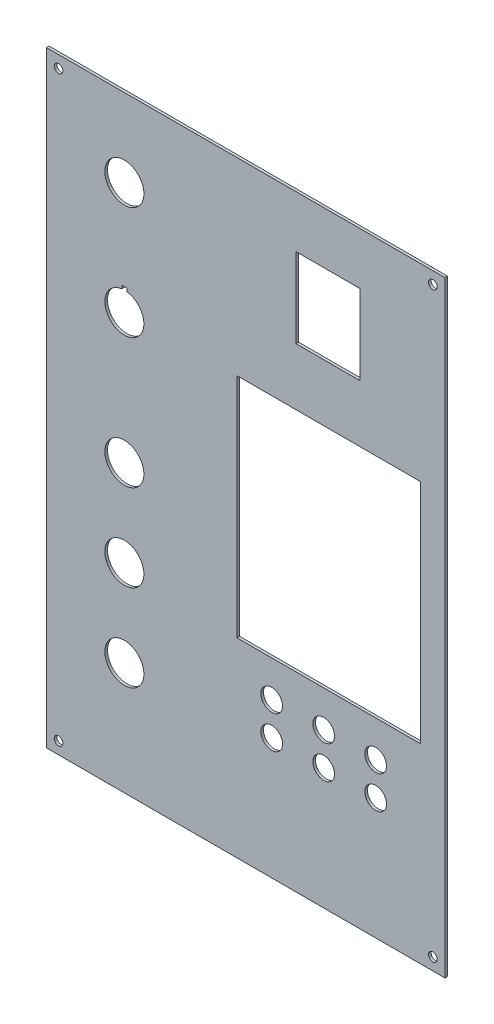
SolidWorks part; units mm, degrees
material "PW80:Md:De:1:18:"
ref_plane "Plan1" through (0, 0, 0) normal (0, 0, 1) x (1, 0, 0)
ref_plane "Plan2" through (0, 0, 0) normal (0, 1, 0) x (1, 0, 0)
ref_plane "Plan3" through (0, 0, 0) normal (1, 0, 0) x (0, 0, -1)
sketch "Esquisse1" plane through (0, 0, 0) normal (0, 0, 1) x (1, 0, 0)
  line L1 (0, 0) -> (230, 0)
  line L2 (0, 0) -> (0, 350)
  line L3 (0, 350) -> (230, 350)
  line L4 (230, 0) -> (230, 350)
extrude "Base-Extrusion" add sketch "Esquisse1" along normal blind 1.5
sketch "Esquisse2" plane through (0, 0, 1.5) normal (0, 0, 1) x (1, 0, 0)
  circle A0 centre (7, 7) radius 2.5
  circle A1 centre (223, 7) radius 2.5
  circle A2 centre (7, 343) radius 2.5
  circle A3 centre (223, 343) radius 2.5
extrude "Enlèv. mat.-Extru.1" cut sketch "Esquisse2" against normal blind 1.5
sketch "Esquisse3" plane through (0, 0, 1.5) normal (0, 0, 1) x (1, 0, 0)
  line L0 (43.5, 251.1496) -> (43.5, 253)
  line L1 (43.5, 253) -> (46.5, 253)
  line L2 (46.5, 251.1496) -> (46.5, 253)
  circle A0 centre (45, 65) radius 11.25
  circle A1 centre (45, 115) radius 11.25
  circle A2 centre (45, 165) radius 11.25
  circle A3 centre (45, 305) radius 11.25
  arc A4 (43.5, 251.1496) -> (46.5, 251.1496) centre (45, 240) ccw
extrude "Enlèv. mat.-Extru.2" cut sketch "Esquisse3" against normal blind 1.5
sketch "Esquisse4" plane through (0, 0, 1.5) normal (0, 0, 1) x (1, 0, 0)
  circle A0 centre (130, 70) radius 6.25
  circle A1 centre (130, 89) radius 6.25
  circle A2 centre (160, 70) radius 6.25
  circle A3 centre (160, 89) radius 6.25
  circle A4 centre (190, 70) radius 6.25
  circle A5 centre (190, 89) radius 6.25
extrude "Enlèv. mat.-Extru.3" cut sketch "Esquisse4" against normal blind 1.5
sketch "Esquisse5" plane through (0, 0, 1.5) normal (0, 0, 1) x (1, 0, 0)
  line L1 (110, 241) -> (216, 241)
  line L2 (110, 241) -> (110, 110)
  line L3 (110, 110) -> (216, 110)
  line L4 (216, 241) -> (216, 110)
extrude "Enlèv. mat.-Extru.4" cut sketch "Esquisse5" against normal blind 1.5
sketch "Esquisse6" plane through (0, 0, 1.5) normal (0, 0, 1) x (1, 0, 0)
  line L1 (144, 320) -> (181, 320)
  line L2 (144, 320) -> (144, 274)
  line L3 (144, 274) -> (181, 274)
  line L4 (181, 320) -> (181, 274)
extrude "Enlèv. mat.-Extru.5" cut sketch "Esquisse6" against normal blind 1.5
